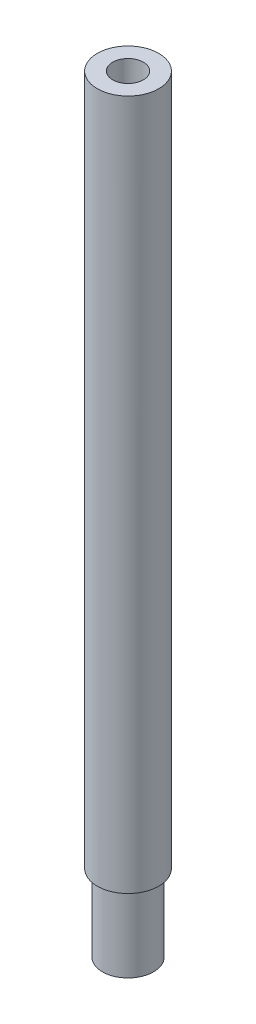
SolidWorks part; units mm, degrees
ref_plane "正面" through (0, 0, 0) normal (0, 0, 1) x (1, 0, 0)
ref_plane "平面" through (0, 0, 0) normal (0, 1, 0) x (1, 0, 0)
ref_plane "右側面" through (0, 0, 0) normal (1, 0, 0) x (0, 0, -1)
sketch "ｽｹｯﾁ1" plane through (0, 0, 0) normal (0, 1, 0) x (1, 0, 0)
  circle A2 centre (0, 0) radius 6
extrude "ﾎﾞｽ - 押し出し2" add sketch "ｽｹｯﾁ1" along normal blind 150 contours A2
sketch "ｽｹｯﾁ3" plane through (0, 150, 0) normal (0, 1, 0) x (1, 0, 0)
  circle A0 centre (0, 0) radius 3
extrude "ｶｯﾄ - 押し出し2" cut sketch "ｽｹｯﾁ3" against normal blind 18 and the other way through all
sketch "ｽｹｯﾁ4" plane through (0, 0, 0) normal (0, 0, 1) x (1, 0, 0)
  line L0 (0, -6.6) -> (0, 6.6) construction
  line L1 (6, 150) -> (-6, 150) construction
  circle A0 centre (0, 142) radius 1.25
  dimension "D1" = 8
extrude "ｶｯﾄ - 押し出し4" cut sketch "ｽｹｯﾁ4" against normal up to next contours A0
sketch "ｽｹｯﾁ5" plane through (0, 0, 0) normal (0, -1, 0) x (1, 0, 0)
  circle A0 centre (0, 0) radius 5
  circle A1 centre (0, 0) radius 6
extrude "ｶｯﾄ - 押し出し5" cut sketch "ｽｹｯﾁ5" against normal blind 15
